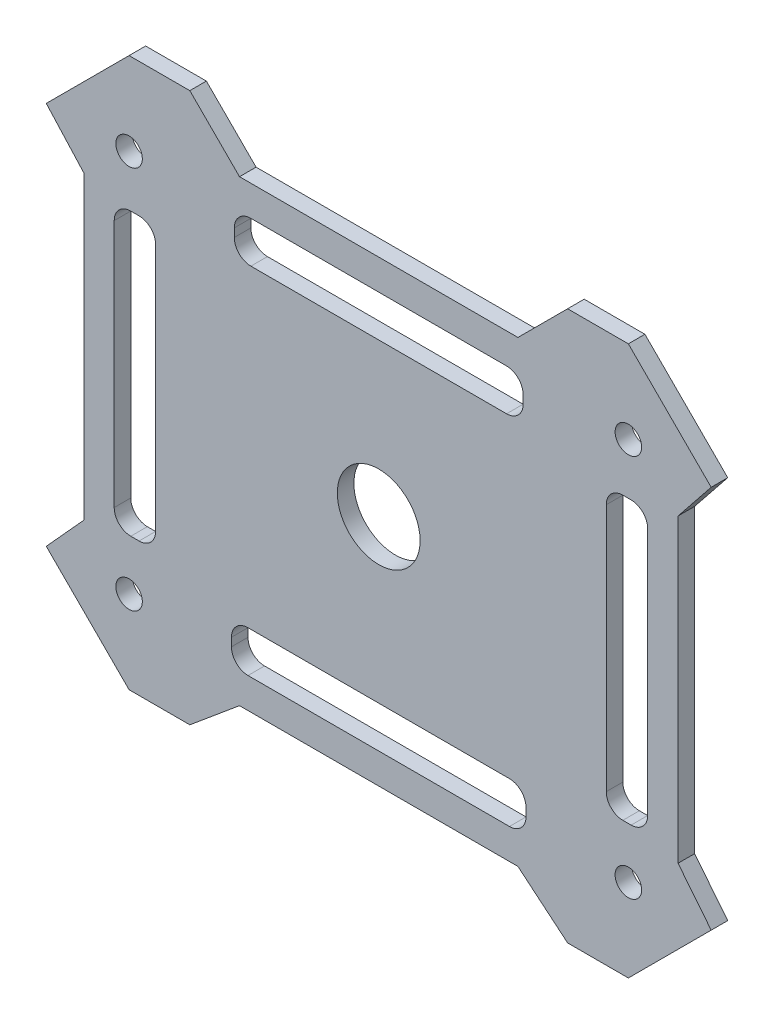
SolidWorks part; units mm, degrees
ref_plane "Front Plane" through (0, 0, 0) normal (0, 0, 1) x (1, 0, 0)
ref_plane "Top Plane" through (0, 0, 0) normal (0, 1, 0) x (1, 0, 0)
ref_plane "Right Plane" through (0, 0, 0) normal (1, 0, 0) x (0, 0, -1)
sketch "Sketch1" plane through (0, 0, 0) normal (0, 0, 1) x (1, 0, 0)
  line L0 (-66.8215, 56.7885) -> (-51.8215, 71.7885)
  line L1 (-31.8215, 62.7885) -> (18.6025, 62.7885)
  line L2 (47.6025, 49.2885) -> (47.6025, -5.1805)
  line L3 (-66.8215, -12.6805) -> (-60.0143, -5.1805)
  line L4 (-40.8215, 71.7885) -> (-31.8215, 62.7885)
  line L5 (-51.8215, 71.7885) -> (-40.8215, 71.7885)
  line L6 (38.6025, 71.7885) -> (53.6025, 56.7885)
  line L7 (-66.8215, -12.6805) -> (-51.8215, -27.6805)
  line L8 (-51.8215, -27.6805) -> (-40.8215, -27.6805)
  line L9 (38.6025, -27.6805) -> (53.6025, -12.6805)
  line L10 (27.6025, -27.6805) -> (38.6025, -27.6805)
  line L11 (27.6025, 71.7885) -> (38.6025, 71.7885)
  line L12 (-60.0143, 49.2885) -> (-66.8215, 56.7885)
  line L14 (18.6025, -20.1805) -> (-31.8215, -20.1805)
  line L15 (47.6025, 49.2885) -> (53.6025, 56.7885)
  line L16 (47.6025, -5.1805) -> (53.6025, -12.6805)
  line L17 (18.6025, 62.7885) -> (27.6025, 71.7885)
  line L18 (-31.8215, -20.1805) -> (-40.8215, -27.6805)
  line L19 (18.6025, -20.1805) -> (27.6025, -27.6805)
  line L20 (-51.5143, 47.554) -> (-50.0143, 47.554)
  line L21 (-54.5143, 44.554) -> (-54.5143, -0.446)
  line L22 (-51.5143, -3.446) -> (-50.0143, -3.446)
  line L23 (-47.0143, 44.554) -> (-47.0143, -0.446)
  line L24 (-29.7649, 57.2885) -> (16.546, 57.2885)
  line L25 (-32.7649, 54.2885) -> (-32.7649, 52.7885)
  line L26 (-29.7649, 49.7885) -> (16.546, 49.7885)
  line L27 (19.546, 54.2885) -> (19.546, 52.7885)
  line L28 (39.1025, 47.554) -> (37.6025, 47.554)
  line L29 (42.1025, 44.554) -> (42.1025, -0.446)
  line L30 (39.1025, -3.446) -> (37.6025, -3.446)
  line L31 (34.6025, 44.554) -> (34.6025, -0.446)
  line L32 (17.068, -14.6805) -> (-30.287, -14.6805)
  line L33 (20.068, -11.6805) -> (20.068, -10.1805)
  line L34 (17.068, -7.1805) -> (-30.287, -7.1805)
  line L35 (-33.287, -11.6805) -> (-33.287, -10.1805)
  line L36 (-60.0143, 49.2885) -> (-60.0143, -5.1805)
  arc A0 (39.1025, -3.446) -> (42.1025, -0.446) centre (39.1025, -0.446) ccw
  arc A1 (34.6025, -0.446) -> (37.6025, -3.446) centre (37.6025, -0.446) ccw
  arc A2 (42.1025, 44.554) -> (39.1025, 47.554) centre (39.1025, 44.554) ccw
  arc A3 (37.6025, 47.554) -> (34.6025, 44.554) centre (37.6025, 44.554) ccw
  arc A4 (16.546, 49.7885) -> (19.546, 52.7885) centre (16.546, 52.7885) ccw
  arc A5 (19.546, 54.2885) -> (16.546, 57.2885) centre (16.546, 54.2885) ccw
  arc A6 (-32.7649, 52.7885) -> (-29.7649, 49.7885) centre (-29.7649, 52.7885) ccw
  arc A7 (-29.7649, 57.2885) -> (-32.7649, 54.2885) centre (-29.7649, 54.2885) ccw
  arc A8 (-47.0143, 44.554) -> (-50.0143, 47.554) centre (-50.0143, 44.554) ccw
  arc A9 (-51.5143, 47.554) -> (-54.5143, 44.554) centre (-51.5143, 44.554) ccw
  arc A10 (-50.0143, -3.446) -> (-47.0143, -0.446) centre (-50.0143, -0.446) ccw
  arc A11 (-54.5143, -0.446) -> (-51.5143, -3.446) centre (-51.5143, -0.446) ccw
  circle A12 centre (-6.6095, 22.054) radius 7.5
  arc A13 (17.068, -14.6805) -> (20.068, -11.6805) centre (17.068, -11.6805) ccw
  arc A14 (20.068, -10.1805) -> (17.068, -7.1805) centre (17.068, -10.1805) ccw
  arc A15 (-30.287, -7.1805) -> (-33.287, -10.1805) centre (-30.287, -10.1805) ccw
  arc A16 (-33.287, -11.6805) -> (-30.287, -14.6805) centre (-30.287, -11.6805) ccw
  circle A17 centre (-51.8215, 56.7885) radius 2.4
  circle A18 centre (38.6025, 56.7885) radius 2.4
  circle A19 centre (38.6025, -12.6805) radius 2.4
  circle A20 centre (-51.8215, -12.6805) radius 2.4
  point P83 (-60.0143, 22.054)
  point P84 (-6.6095, -20.1805)
  point P89 (-46.3215, 71.7885)
  point P90 (-6.6095, 62.7885)
  point P94 (-6.6095, 57.2885)
  point P95 (-6.6095, -7.1805)
  point P96 (-6.6095, 49.7885)
  point P99 (34.6025, 22.054)
  point P100 (47.6025, 22.054)
  point P103 (-47.0143, 22.054)
  dimension "D1" = 15
  dimension "D2" = 15
  dimension "D3" = 15
  dimension "D4" = 15
  dimension "D5" = 15
  dimension "D6" = 15
  dimension "D7" = 15
  dimension "D8" = 15
  dimension "D9" = 9
  dimension "D10" = 90.424
  dimension "D11" = 11
  dimension "D12" = 11
  dimension "D13" = 69.469
  dimension "D14" = 9
  dimension "D15" = 9
  dimension "D16" = 7.5
  dimension "D17" = 7.5
  dimension "D18" = 13
  dimension "D19" = 13
  dimension "D20" = 13
  dimension "D21" = 13
extrude "Boss-Extrude1" add sketch "Sketch1" along normal blind 3
